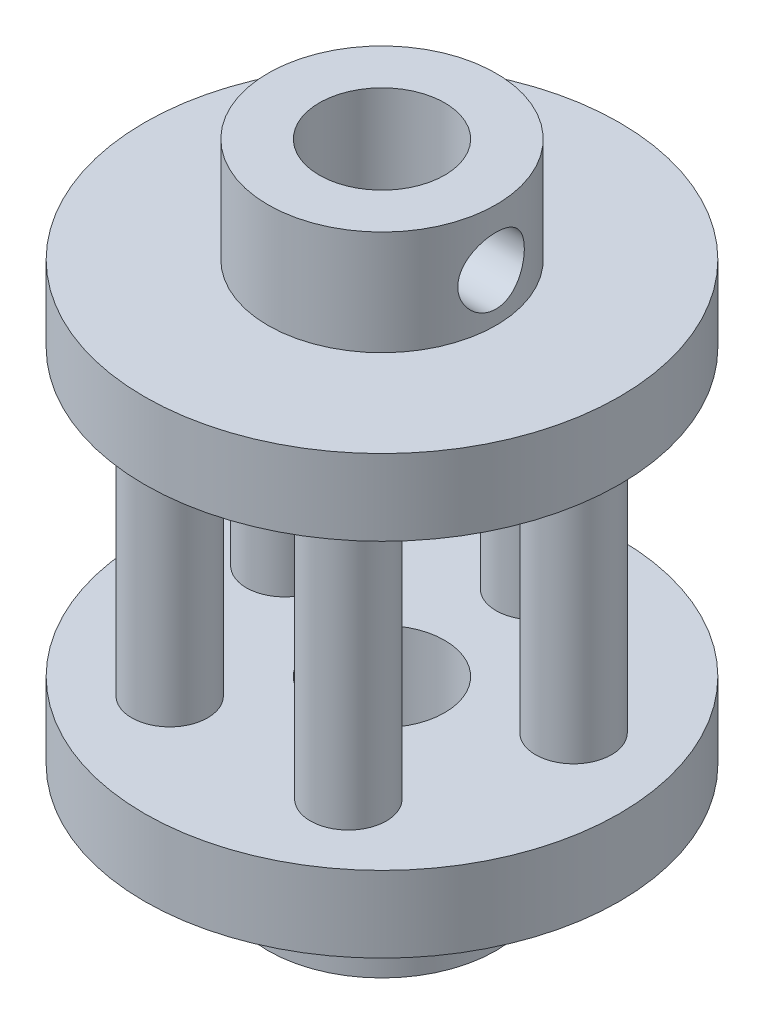
SolidWorks part; units mm, degrees
ref_plane "Ön Düzlem" through (0, 0, 0) normal (0, 0, 1) x (1, 0, 0)
ref_plane "Üst Düzlem" through (0, 0, 0) normal (0, 1, 0) x (1, 0, 0)
ref_plane "Sağ Düzlem" through (0, 0, 0) normal (1, 0, 0) x (0, 0, -1)
sketch "Sketch1" plane through (0, 0, 0) normal (0, 1, 0) x (1, 0, 0)
  circle A0 centre (0, 0) radius 12.5
  circle A1 centre (0, 0) radius 3.3
  dimension "D1" = 25
  dimension "D2" = 6.6
extrude "Boss-Extrude1" add sketch "Sketch1" along normal blind 4
sketch "Sketch8" plane through (0, 0, 0) normal (0, -1, 0) x (1, 0, 0)
  circle A0 centre (0, 0) radius 3.3
  circle A1 centre (0, 0) radius 6
  dimension "D1" = 12
  dimension "D2" = 6.6
extrude "Boss-Extrude7" add sketch "Sketch8" along normal blind 5.5
sketch "Sketch9" plane through (0, 4, 0) normal (0, 1, 0) x (1, 0, 0)
  circle A0 centre (0, 0) radius 8
  circle A1 centre (0, 8) radius 2
  circle A2 centre (7.6085, 2.4721) radius 2
  circle A3 centre (4.7023, -6.4721) radius 2
  circle A4 centre (-4.7023, -6.4721) radius 2
  circle A5 centre (-7.6085, 2.4721) radius 2
  point P15 (0, 0)
  dimension "D1" = 16
  dimension "D2" = 4
  dimension "D3" = 5
extrude "Boss-Extrude8" add sketch "Sketch9" along normal blind 15 contours A0 A5 | A0 A5 | A0 A4 | A0 A4 | A0 A3 | A0 A3 | A0 A2 | A0 A2 | A0 A1 | A0 A1
sketch "Sketch10" plane through (0, 19, 0) normal (0, 1, 0) x (1, 0, 0)
  circle A0 centre (0, 0) radius 3.3
  circle A1 centre (0, 0) radius 12.5
  dimension "D1" = 6.6
extrude "Boss-Extrude9" add sketch "Sketch10" along normal blind 4
sketch "Sketch11" plane through (0, 23, 0) normal (0, 1, 0) x (1, 0, 0)
  circle A0 centre (0, 0) radius 3.3
  circle A1 centre (0, 0) radius 6
  dimension "D1" = 12
  dimension "D2" = 6.6
extrude "Boss-Extrude10" add sketch "Sketch11" along normal blind 5.5
ref_plane "Plane3" through (6, 0, 0) normal (1, 0, 0) x (0, 0, -1)
sketch "Sketch12" plane through (6, 0, 0) normal (1, 0, 0) x (0, 0, -1)
  circle A0 centre (0, 25.5) radius 1.75
  dimension "D1" = 3.5
extrude "Cut-Extrude3" cut sketch "Sketch12" against normal up to next
ref_plane "Plane4" through (6, 0, 0) normal (1, 0, 0) x (0, 0, -1)
sketch "Sketch13" plane through (6, 0, 0) normal (1, 0, 0) x (0, 0, -1)
  circle A0 centre (0, -2.5) radius 1.75
  dimension "D1" = 3.5
extrude "Cut-Extrude4" cut sketch "Sketch13" against normal up to next
